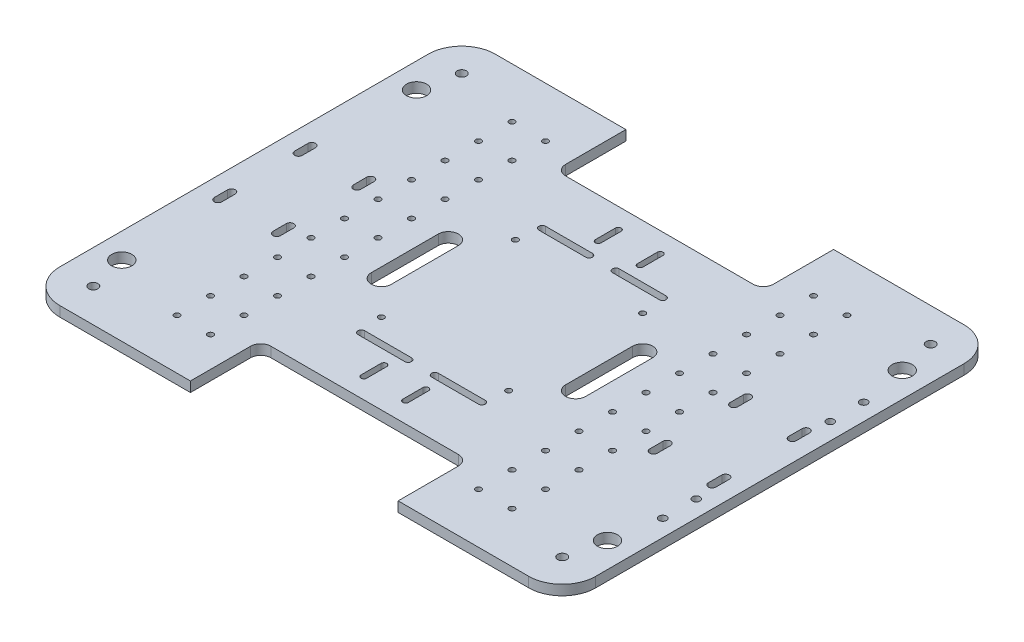
SolidWorks part; units mm, degrees
material "6061-T6 (SS)"
ref_plane "Front Plane" through (0, 0, 0) normal (0, 0, 1) x (1, 0, 0)
ref_plane "Top Plane" through (0, 0, 0) normal (0, 1, 0) x (1, 0, 0)
ref_plane "Right Plane" through (0, 0, 0) normal (1, 0, 0) x (0, 0, -1)
sketch "SK_Plate" plane through (0, 0, 0) normal (0, 1, 0) x (1, 0, 0)
  line L0 (160, -110) -> (160, 110)
  line L1 (140, 130) -> (62, 130)
  line L2 (62, 130) -> (62, 94)
  line L3 (56, 88) -> (-56, 88)
  line L4 (-62, 94) -> (-62, 130)
  line L5 (-62, 130) -> (-140, 130)
  line L6 (-160, 110) -> (-160, -110)
  line L7 (-140, -130) -> (-62, -130)
  line L8 (-62, -130) -> (-62, -94)
  line L9 (-56, -88) -> (56, -88)
  line L10 (62, -94) -> (62, -130)
  line L11 (62, -130) -> (140, -130)
  arc A0 (160, 110) -> (140, 130) centre (140, 110) ccw
  arc A1 (62, 94) -> (56, 88) centre (56, 94) cw
  arc A2 (-56, 88) -> (-62, 94) centre (-56, 94) cw
  arc A3 (-140, 130) -> (-160, 110) centre (-140, 110) ccw
  arc A4 (-160, -110) -> (-140, -130) centre (-140, -110) ccw
  arc A5 (-62, -94) -> (-56, -88) centre (-56, -94) cw
  arc A6 (56, -88) -> (62, -94) centre (56, -94) cw
  arc A7 (140, -130) -> (160, -110) centre (140, -110) ccw
extrude "Plate" add sketch "SK_Plate" along normal blind 6
sketch "SK_MotorMounts" plane through (0, 0, 0) normal (0, 1, 0) x (1, 0, 0)
  line L0 (-14.2, 64) -> (-14.2, 76)
  line L1 (-10.8, 76) -> (-10.8, 64)
  line L2 (10.8, 64) -> (10.8, 76)
  line L3 (14.2, 76) -> (14.2, 64)
  line L4 (-10.8, -64) -> (-10.8, -76)
  line L5 (-14.2, -76) -> (-14.2, -64)
  line L6 (14.2, -64) -> (14.2, -76)
  line L7 (10.8, -76) -> (10.8, -64)
  arc A0 (-14.2, 76) -> (-10.8, 76) centre (-12.5, 76) cw
  arc A1 (-10.8, 64) -> (-14.2, 64) centre (-12.5, 64) cw
  arc A2 (10.8, 76) -> (14.2, 76) centre (12.5, 76) cw
  arc A3 (14.2, 64) -> (10.8, 64) centre (12.5, 64) cw
  arc A4 (-10.8, -76) -> (-14.2, -76) centre (-12.5, -76) cw
  arc A5 (-14.2, -64) -> (-10.8, -64) centre (-12.5, -64) cw
  arc A6 (14.2, -76) -> (10.8, -76) centre (12.5, -76) cw
  arc A7 (10.8, -64) -> (14.2, -64) centre (12.5, -64) cw
extrude "Cut_MotorMounts_M3" cut sketch "SK_MotorMounts" against normal through all and the other way through all
sketch "SK_CasterMounts" plane through (0, 0, 0) normal (0, 1, 0) x (1, 0, 0)
  line L0 (110.25, 20) -> (110.25, 28)
  line L1 (114.75, 28) -> (114.75, 20)
  line L2 (114.75, -20) -> (114.75, -28)
  line L3 (110.25, -28) -> (110.25, -20)
  line L4 (145.25, 20) -> (145.25, 28)
  line L5 (149.75, 28) -> (149.75, 20)
  line L6 (149.75, -20) -> (149.75, -28)
  line L7 (145.25, -28) -> (145.25, -20)
  line L8 (-149.75, 20) -> (-149.75, 28)
  line L9 (-145.25, 28) -> (-145.25, 20)
  line L10 (-145.25, -20) -> (-145.25, -28)
  line L11 (-149.75, -28) -> (-149.75, -20)
  line L12 (-114.75, 20) -> (-114.75, 28)
  line L13 (-110.25, 28) -> (-110.25, 20)
  line L14 (-110.25, -20) -> (-110.25, -28)
  line L15 (-114.75, -28) -> (-114.75, -20)
  arc A0 (110.25, 28) -> (114.75, 28) centre (112.5, 28) cw
  arc A1 (114.75, 20) -> (110.25, 20) centre (112.5, 20) cw
  arc A2 (114.75, -28) -> (110.25, -28) centre (112.5, -28) cw
  arc A3 (110.25, -20) -> (114.75, -20) centre (112.5, -20) cw
  arc A4 (145.25, 28) -> (149.75, 28) centre (147.5, 28) cw
  arc A5 (149.75, 20) -> (145.25, 20) centre (147.5, 20) cw
  arc A6 (149.75, -28) -> (145.25, -28) centre (147.5, -28) cw
  arc A7 (145.25, -20) -> (149.75, -20) centre (147.5, -20) cw
  arc A8 (-149.75, 28) -> (-145.25, 28) centre (-147.5, 28) cw
  arc A9 (-145.25, 20) -> (-149.75, 20) centre (-147.5, 20) cw
  arc A10 (-145.25, -28) -> (-149.75, -28) centre (-147.5, -28) cw
  arc A11 (-149.75, -20) -> (-145.25, -20) centre (-147.5, -20) cw
  arc A12 (-114.75, 28) -> (-110.25, 28) centre (-112.5, 28) cw
  arc A13 (-110.25, 20) -> (-114.75, 20) centre (-112.5, 20) cw
  arc A14 (-110.25, -28) -> (-114.75, -28) centre (-112.5, -28) cw
  arc A15 (-114.75, -20) -> (-110.25, -20) centre (-112.5, -20) cw
extrude "Cut_CasterMounts_M4" cut sketch "SK_CasterMounts" against normal through all and the other way through all
sketch "SK_BatteryBay" plane through (0, 0, 0) normal (0, 1, 0) x (1, 0, 0)
  line L0 (-36, 56) -> (-8, 56)
  line L1 (-8, 52) -> (-36, 52)
  line L2 (-36, -52) -> (-8, -52)
  line L3 (-8, -56) -> (-36, -56)
  line L4 (8, 56) -> (36, 56)
  line L5 (36, 52) -> (8, 52)
  line L6 (8, -52) -> (36, -52)
  line L7 (36, -56) -> (8, -56)
  arc A0 (-8, 56) -> (-8, 52) centre (-8, 54) cw
  arc A1 (-36, 52) -> (-36, 56) centre (-36, 54) cw
  arc A2 (-8, -52) -> (-8, -56) centre (-8, -54) cw
  arc A3 (-36, -56) -> (-36, -52) centre (-36, -54) cw
  arc A4 (36, 56) -> (36, 52) centre (36, 54) cw
  arc A5 (8, 52) -> (8, 56) centre (8, 54) cw
  arc A6 (36, -52) -> (36, -56) centre (36, -54) cw
  arc A7 (8, -56) -> (8, -52) centre (8, -54) cw
  circle A8 centre (-38, 40) radius 1.7
  circle A9 centre (-38, -40) radius 1.7
  circle A10 centre (38, 40) radius 1.7
  circle A11 centre (38, -40) radius 1.7
extrude "Cut_BatteryBay" cut sketch "SK_BatteryBay" against normal through all and the other way through all
sketch "SK_CablePassThru" plane through (0, 0, 0) normal (0, 1, 0) x (1, 0, 0)
  line L0 (52, -20) -> (52, 20)
  line L1 (64, 20) -> (64, -20)
  line L2 (-64, -20) -> (-64, 20)
  line L3 (-52, 20) -> (-52, -20)
  arc A0 (52, 20) -> (64, 20) centre (58, 20) cw
  arc A1 (64, -20) -> (52, -20) centre (58, -20) cw
  arc A2 (-64, 20) -> (-52, 20) centre (-58, 20) cw
  arc A3 (-52, -20) -> (-64, -20) centre (-58, -20) cw
extrude "Cut_CablePassThru" cut sketch "SK_CablePassThru" against normal through all and the other way through all
sketch "SK_ElecGrid_M3" plane through (0, 0, 0) normal (0, 1, 0) x (1, 0, 0)
  circle A0 centre (-100, -100) radius 1.7
  circle A1 centre (-100, -80) radius 1.7
  circle A2 centre (-100, -60) radius 1.7
  circle A3 centre (-100, -40) radius 1.7
  circle A4 centre (-100, -20) radius 1.7
  circle A5 centre (-100, 0) radius 1.7
  circle A6 centre (-100, 20) radius 1.7
  circle A7 centre (-100, 40) radius 1.7
  circle A8 centre (-100, 60) radius 1.7
  circle A9 centre (-100, 80) radius 1.7
  circle A10 centre (-100, 100) radius 1.7
  circle A11 centre (-80, -100) radius 1.7
  circle A12 centre (-80, -80) radius 1.7
  circle A13 centre (-80, -60) radius 1.7
  circle A14 centre (-80, -40) radius 1.7
  circle A15 centre (-80, -20) radius 1.7
  circle A16 centre (-80, 0) radius 1.7
  circle A17 centre (-80, 20) radius 1.7
  circle A18 centre (-80, 40) radius 1.7
  circle A19 centre (-80, 60) radius 1.7
  circle A20 centre (-80, 80) radius 1.7
  circle A21 centre (-80, 100) radius 1.7
  circle A22 centre (80, -100) radius 1.7
  circle A23 centre (80, -80) radius 1.7
  circle A24 centre (80, -60) radius 1.7
  circle A25 centre (80, -40) radius 1.7
  circle A26 centre (80, -20) radius 1.7
  circle A27 centre (80, 0) radius 1.7
  circle A28 centre (80, 20) radius 1.7
  circle A29 centre (80, 40) radius 1.7
  circle A30 centre (80, 60) radius 1.7
  circle A31 centre (80, 80) radius 1.7
  circle A32 centre (80, 100) radius 1.7
  circle A33 centre (100, -100) radius 1.7
  circle A34 centre (100, -80) radius 1.7
  circle A35 centre (100, -60) radius 1.7
  circle A36 centre (100, -40) radius 1.7
  circle A37 centre (100, -20) radius 1.7
  circle A38 centre (100, 0) radius 1.7
  circle A39 centre (100, 20) radius 1.7
  circle A40 centre (100, 40) radius 1.7
  circle A41 centre (100, 60) radius 1.7
  circle A42 centre (100, 80) radius 1.7
  circle A43 centre (100, 100) radius 1.7
extrude "Cut_ElecGrid_M3" cut sketch "SK_ElecGrid_M3" against normal through all and the other way through all
sketch "SK_DeckPosts_M5" plane through (0, 0, 0) normal (0, 1, 0) x (1, 0, 0)
  circle A0 centre (140, 110) radius 2.75
  circle A1 centre (140, -110) radius 2.75
  circle A2 centre (-140, 110) radius 2.75
  circle A3 centre (-140, -110) radius 2.75
extrude "Cut_DeckPosts_M5" cut sketch "SK_DeckPosts_M5" against normal through all and the other way through all
sketch "SK_CliffSensors" plane through (0, 0, 0) normal (0, 1, 0) x (1, 0, 0)
  circle A0 centre (145, 88) radius 6
  circle A1 centre (145, -88) radius 6
  circle A2 centre (-145, 88) radius 6
  circle A3 centre (-145, -88) radius 6
extrude "Cut_CliffSensorWindows" cut sketch "SK_CliffSensors" against normal through all and the other way through all
sketch "SK_ChargeContacts" plane through (0, 0, 0) normal (0, 1, 0) x (1, 0, 0)
  circle A0 centre (150, 40) radius 2.25
  circle A1 centre (150, 60) radius 2.25
  circle A2 centre (150, -40) radius 2.25
  circle A3 centre (150, -60) radius 2.25
extrude "Cut_ChargeContacts_M4" cut sketch "SK_ChargeContacts" against normal through all and the other way through all
